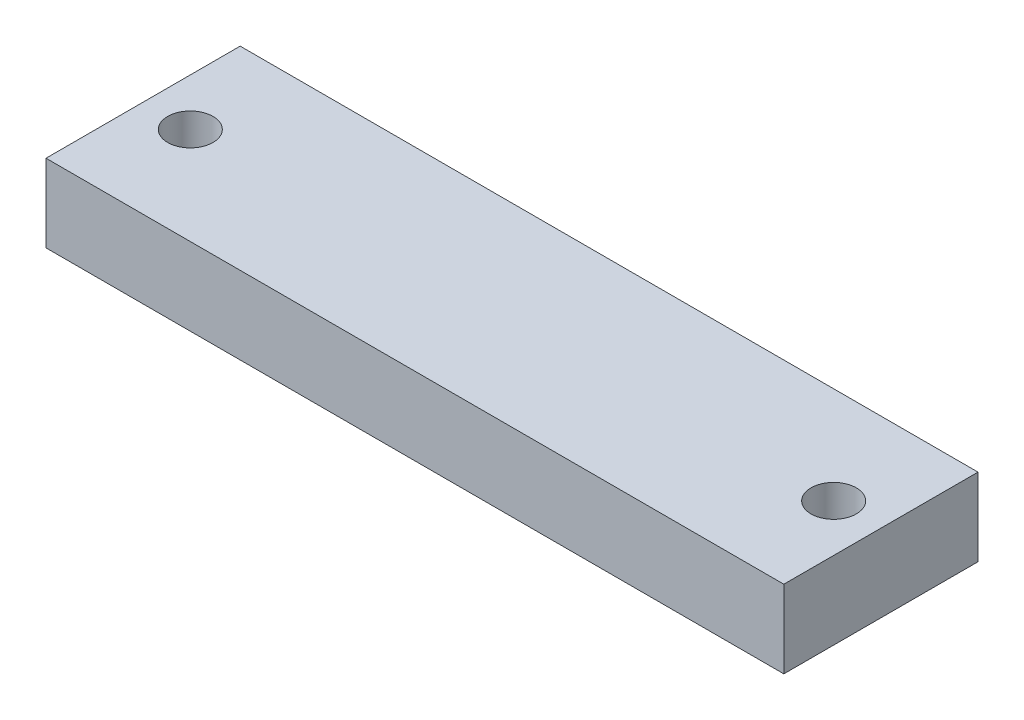
SolidWorks part; units mm, degrees
ref_plane "Front Plane" through (0, 0, 0) normal (0, 0, 1) x (1, 0, 0)
ref_plane "Top Plane" through (0, 0, 0) normal (0, 1, 0) x (1, 0, 0)
ref_plane "Right Plane" through (0, 0, 0) normal (1, 0, 0) x (0, 0, -1)
sketch "Sketch1" plane through (0, 0, 0) normal (0, 1, 0) x (1, 0, 0)
  line L1 (0, 0) -> (57, 0)
  line L2 (0, 0) -> (0, -15)
  line L3 (0, -15) -> (57, -15)
  line L4 (57, 0) -> (57, -15)
  circle A0 centre (3.65, -7.5) radius 1.75
  circle A1 centre (53.35, -7.5) radius 1.75
  dimension "D3" = 3.5
  dimension "D4" = 3.5
  dimension "D1" = 57
  dimension "D2" = 15
  dimension "D5" = 3.65
  dimension "D6" = 7.5
  dimension "D7" = 3.65
  dimension "D8" = 7.5
extrude "Boss-Extrude1" add sketch "Sketch1" along normal blind 6
